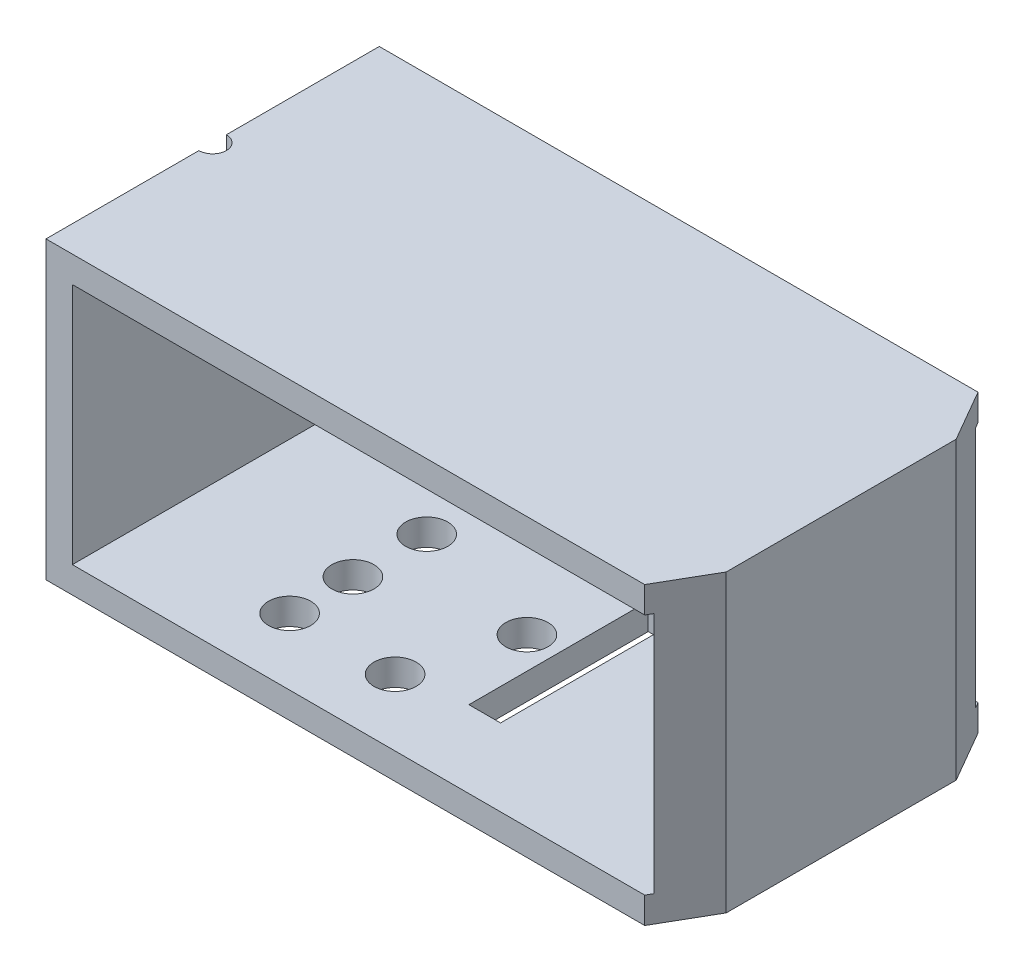
SolidWorks part; units mm, degrees
ref_plane "Plano frontal" through (0, 0, 0) normal (0, 0, 1) x (1, 0, 0)
ref_plane "Plano superior" through (0, 0, 0) normal (0, 1, 0) x (1, 0, 0)
ref_plane "Plano direito" through (0, 0, 0) normal (1, 0, 0) x (0, 0, -1)
sketch "Vista Frontal" plane through (0, 0, 0) normal (0, 0, 1) x (1, 0, 0)
  line L1 (-27.3, 11.5) -> (27.3, 11.5)
  line L2 (-27.3, 11.5) -> (-27.3, -11.5)
  line L3 (-27.3, -11.5) -> (27.3, -11.5)
  line L4 (27.3, 11.5) -> (27.3, -11.5)
  line L5 (-27.3, 11.5) -> (27.3, -11.5) construction
  line L6 (-27.3, -11.5) -> (27.3, 11.5) construction
  line L7 (-29.8, 14) -> (29.8, 14)
  line L8 (-29.8, 14) -> (-29.8, -14)
  line L9 (-29.8, -14) -> (29.8, -14)
  line L10 (29.8, 14) -> (29.8, -14)
  line L11 (-29.8, 14) -> (29.8, -14) construction
  line L12 (-29.8, -14) -> (29.8, 14) construction
  point P0 (0, 0)
  point P6 (0, 0)
  dimension "D1" = 2.5
  dimension "D2" = 28
  dimension "D3" = 2.5
  dimension "D4" = 59.6
extrude "Corpo do Modulo" add sketch "Vista Frontal" along normal mid plane 31.6
sketch "Esboço3" plane through (0, 14, 0) normal (0, 1, 0) x (1, 0, 0)
  line L0 (-29.8, -15.8) -> (-29.8, 15.8) construction
  line L1 (26.971, -15.8) -> (29.8, -10.9)
  line L2 (-29.8, -15.8) -> (29.8, -15.8) construction
  line L3 (29.8, -15.8) -> (29.8, 15.8) construction
  line L4 (29.8, -10.9) -> (29.8, -15.8)
  line L5 (29.8, -15.8) -> (26.971, -15.8)
  line L6 (29.8, 0) -> (-29.8, 0) construction
  line L7 (29.8, 15.8) -> (26.971, 15.8)
  line L8 (29.8, 10.9) -> (29.8, 15.8)
  line L9 (26.971, 15.8) -> (29.8, 10.9)
  circle A0 centre (-29.8, 0) radius 1.3
  dimension "D1" = 2.6
  dimension "D2" = 60
  dimension "D3" = 4.9
extrude "Corte-extrusão1" cut sketch "Esboço3" against normal through all
sketch "Esboço4" plane through (0, -14, 0) normal (0, -1, 0) x (1, 0, 0)
  line L0 (-28.5, 0) -> (29.8, 0) construction
  line L1 (29.8, 10.9) -> (29.8, -10.9) construction
  line L2 (-29.8, -1.3) -> (-29.8, -15.8) construction
  line L3 (-3, 9.5) -> (-29.8, 9.5) construction
  line L4 (-29.8, 15.8) -> (-29.8, 1.3) construction
  line L5 (-13, 9.5) -> (-13, 0) construction
  line L7 (3, 8.5) -> (6, 8.5)
  line L8 (3, 8.5) -> (3, -8.5)
  line L9 (3, -8.5) -> (6, -8.5)
  line L10 (6, 8.5) -> (6, -8.5)
  line L11 (3, 8.5) -> (6, -8.5) construction
  line L12 (3, -8.5) -> (6, 8.5) construction
  arc A0 (-29.8, -1.3) -> (-29.8, 1.3) centre (-29.8, 0) ccw construction
  circle A1 centre (0, 0) radius 2
  circle A2 centre (-3, 9.5) radius 2
  circle A3 centre (-13, 9.5) radius 2
  circle A4 centre (-13, 3.5) radius 2
  circle A5 centre (-13, -3.5) radius 2
  circle A6 centre (-13, -9.5) radius 2
  circle A7 centre (-3, -9.5) radius 2
  point P23 (4.5, 0)
  dimension "D1" = 4
  dimension "D2" = 4
  dimension "D3" = 29.8
  dimension "D4" = 9.5
  dimension "D5" = 3
  dimension "D6" = 4
  dimension "D7" = 4
  dimension "D8" = 10
  dimension "D9" = 6
  dimension "D10" = 17
  dimension "D11" = 3
  dimension "D12" = 4.5
extrude "Corte-extrusão2" cut sketch "Esboço4" against normal blind 3.6
